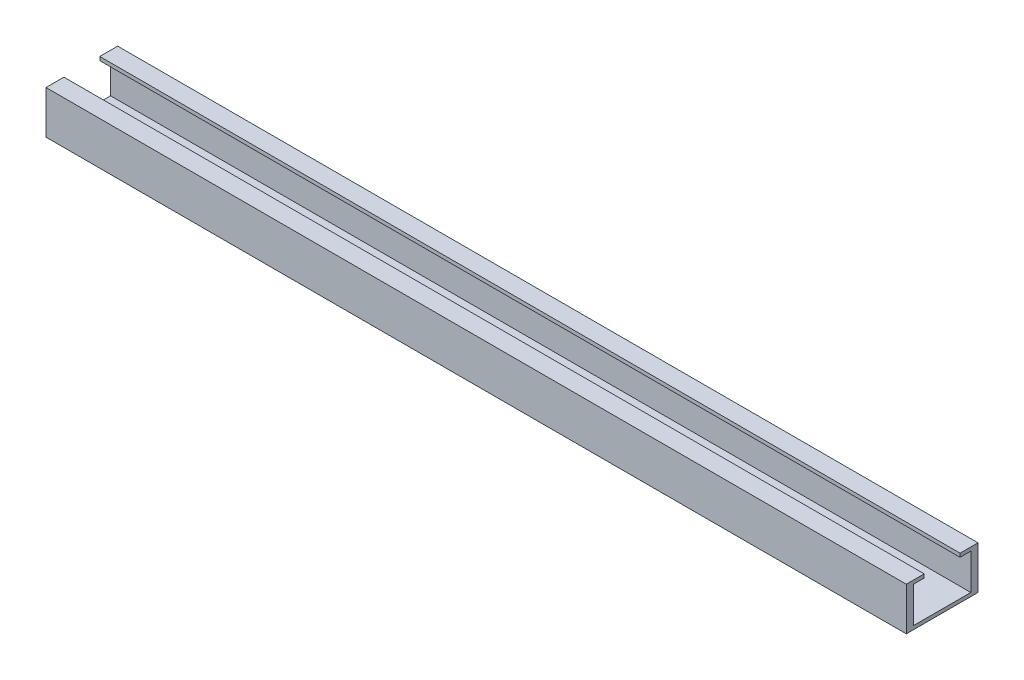
SolidWorks part; units mm, degrees
ref_plane "Front Plane" through (0, 0, 0) normal (0, 0, 1) x (1, 0, 0)
ref_plane "Top Plane" through (0, 0, 0) normal (0, 1, 0) x (1, 0, 0)
ref_plane "Right Plane" through (0, 0, 0) normal (1, 0, 0) x (0, 0, -1)
sketch "Sketch1" plane through (0, 0, 0) normal (0, 1, 0) x (1, 0, 0)
  line L1 (-279.5229, 32.4056) -> (320.4771, 32.4056)
  line L2 (-279.5229, 32.4056) -> (-279.5229, -17.5944)
  line L3 (-279.5229, -17.5944) -> (320.4771, -17.5944)
  line L4 (320.4771, 32.4056) -> (320.4771, -17.5944)
  dimension "D1" = 600
  dimension "3" = 50
extrude "Boss-Extrude1" add sketch "Sketch1" along normal blind 30
sketch "Sketch2" plane through (-279.5229, 0, 0) normal (-1, 0, 0) x (0, 0, 1)
  line L0 (17.5944, 30) -> (17.5944, 0) construction
  line L1 (-27.4056, 27.5) -> (12.5944, 27.5)
  line L2 (-27.4056, 27.5) -> (-27.4056, 2.5)
  line L3 (-27.4056, 2.5) -> (12.5944, 2.5)
  line L4 (12.5944, 27.5) -> (12.5944, 2.5)
  line L5 (-32.4056, 30) -> (17.5944, 30) construction
  dimension "D1" = 40
  dimension "D2" = 25
  dimension "D3" = 5
  dimension "D4" = 2.5
extrude "Cut-Extrude1" cut sketch "Sketch2" against normal through all
sketch "Sketch3" plane through (0, 30, 0) normal (0, 1, 0) x (1, 0, 0)
  line L0 (-279.5229, 32.4056) -> (-279.5229, -17.5944) construction
  line L1 (-279.5229, 19.9056) -> (320.4771, 19.9056)
  line L2 (-279.5229, 19.9056) -> (-279.5229, -5.0944)
  line L3 (-279.5229, -5.0944) -> (320.4771, -5.0944)
  line L4 (320.4771, 19.9056) -> (320.4771, -5.0944)
  line L5 (320.4771, -17.5944) -> (320.4771, 32.4056) construction
  line L6 (320.4771, 32.4056) -> (-279.5229, 32.4056) construction
  dimension "D1" = 25
  dimension "D2" = 12.5
extrude "Cut-Extrude2" cut sketch "Sketch3" against normal blind 20
